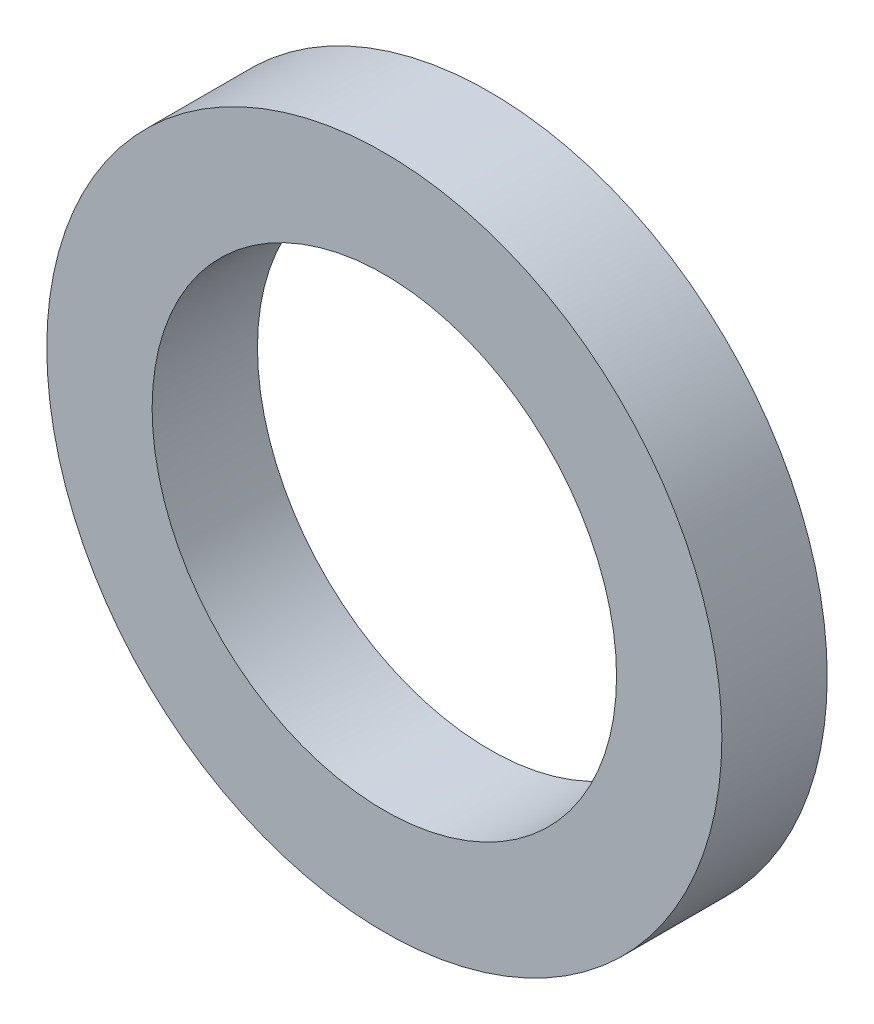
SolidWorks part; units mm, degrees
ref_plane "Front Plane" through (0, 0, 0) normal (0, 0, 1) x (1, 0, 0)
ref_plane "Top Plane" through (0, 0, 0) normal (0, 1, 0) x (1, 0, 0)
ref_plane "Right Plane" through (0, 0, 0) normal (1, 0, 0) x (0, 0, -1)
sketch "Sketch1" plane through (0, 0, 0) normal (0, 0, 1) x (1, 0, 0)
  line L0 (13.9055, 0) -> (52.0055, 0)
  line L1 (52.0055, 0) -> (52.0055, 25.4)
  line L2 (52.0055, 25.4) -> (26.6055, 76.2)
  line L3 (26.6055, 76.2) -> (13.9055, 76.2)
  line L4 (13.9055, 76.2) -> (13.9055, 63.5)
  line L8 (13.9055, 25.4) -> (13.9055, 0)
  line L9 (13.9055, 63.5) -> (22.1886, 51.6705)
  line L10 (22.1886, 51.6705) -> (22.1886, 37.2295)
  line L11 (22.1886, 37.2295) -> (13.9055, 25.4)
  line L12 (0, 0) -> (0, 106.6645) construction
  line L13 (-22.1886, 37.2295) -> (-13.9055, 25.4)
  line L14 (-22.1886, 51.6705) -> (-22.1886, 37.2295)
  line L15 (-13.9055, 63.5) -> (-22.1886, 51.6705)
  line L16 (-13.9055, 25.4) -> (-13.9055, 0)
  line L17 (-13.9055, 76.2) -> (-13.9055, 63.5)
  line L18 (-26.6055, 76.2) -> (-13.9055, 76.2)
  line L19 (-52.0055, 25.4) -> (-26.6055, 76.2)
  line L20 (-52.0055, 0) -> (-52.0055, 25.4)
  line L21 (-13.9055, 0) -> (-52.0055, 0)
  line L24 (-7.493, 16.8) -> (7.493, 16.8) construction
  line L25 (-7.493, 33.6) -> (7.493, 33.6) construction
  line L26 (-7.493, 33.6) -> (-7.493, 0) construction
  line L27 (-7.493, 0) -> (7.493, 0) construction
  line L28 (7.493, 33.6) -> (7.493, 0) construction
  line L30 (-33.493, 24.8) -> (-17.493, 24.8) construction
  line L31 (-33.493, 24.8) -> (-33.493, 8.8) construction
  line L32 (-33.493, 8.8) -> (-17.493, 8.8) construction
  line L33 (-17.493, 24.8) -> (-17.493, 8.8) construction
  line L34 (-33.493, 24.8) -> (-17.493, 8.8) construction
  line L35 (-33.493, 8.8) -> (-17.493, 24.8) construction
  line L36 (17.493, 24.8) -> (33.493, 24.8) construction
  line L37 (17.493, 24.8) -> (17.493, 8.8) construction
  line L38 (17.493, 8.8) -> (33.493, 8.8) construction
  line L39 (33.493, 24.8) -> (33.493, 8.8) construction
  line L40 (17.493, 24.8) -> (33.493, 8.8) construction
  line L41 (17.493, 8.8) -> (33.493, 24.8) construction
  circle A0 centre (-25.493, 16.8) radius 18 construction
  circle A1 centre (25.493, 16.8) radius 18 construction
  circle A2 centre (-33.493, 8.8) radius 2
  circle A3 centre (-17.493, 8.8) radius 2
  circle A4 centre (17.493, 8.8) radius 2
  circle A5 centre (33.493, 8.8) radius 2
  point P26 (0, 0)
  point P31 (-25.493, 16.8)
  point P32 (0, 16.8)
  dimension "D8" = 36
  dimension "D12" = 4
  dimension "D13" = 1.5875
  dimension "D2" = 38.1
  dimension "D3" = 25.4
  dimension "D4" = 12.7
  dimension "D5" = 38.1
  dimension "D6" = 145
  dimension "D7" = 145
  dimension "D9" = 14.986
  dimension "D10" = 33.6
  dimension "D11" = 16
extrude "Boss-Extrude1" add sketch "Sketch1" along normal mid plane 12.7 contours L10 L11 L8 L0 L1 L2 L3 L4 L9 A5 A4 | A4 | A5
sketch "Sketch2" plane through (0, 0, 0) normal (0, 0, 1) x (1, 0, 0)
  circle A0 centre (25.493, 16.8) radius 7
  dimension "D1" = 14
extrude "Cut-Extrude1" cut sketch "Sketch2" against normal through all both and the other way through all
sketch "Sketch5" plane through (0, 0, 6.35) normal (0, 0, 1) x (1, 0, 0)
  circle A0 centre (25.493, 16.8) radius 7 construction
  circle A1 centre (25.493, 16.8) radius 7
extrude "Boss-Extrude2" add sketch "Sketch5" along normal blind 31.75 and the other way up to surface (12.7 mm away) separate body other way up to face at (32.493, 16.8, -6.35)
ref_plane "Plane1" through (0, 0, 15.875) normal (0, 0, 1) x (1, 0, 0)
sketch "Sketch6" plane through (0, 0, 15.875) normal (0, 0, 1) x (1, 0, 0)
  line L0 (14.3805, 0) -> (-14.3805, 0)
  line L1 (14.3805, 30.15) -> (36.6055, 30.15)
  line L2 (14.3805, 30.15) -> (14.3805, 0)
  line L3 (14.3805, -22.225) -> (36.6055, -22.225)
  line L4 (36.6055, 30.15) -> (36.6055, -22.225)
  line L5 (36.6055, -22.225) -> (14.3805, -22.225)
  line L13 (14.3805, 0) -> (14.3805, -22.225) construction
  line L14 (25.493, 30.15) -> (25.493, -22.225) construction
  line L15 (0, 0) -> (0, -22.225)
  line L16 (-14.3805, -22.225) -> (14.3805, -22.225)
  line L17 (0, 0) -> (0, 106.6645) construction
  line L18 (0, 0) -> (0, 106.6645) construction
  line L19 (-25.493, 30.15) -> (-25.493, -22.225) construction
  line L20 (-14.3805, 0) -> (-14.3805, -22.225) construction
  line L22 (-36.6055, -22.225) -> (-14.3805, -22.225)
  line L23 (-36.6055, 30.15) -> (-36.6055, -22.225)
  line L24 (-14.3805, -22.225) -> (-36.6055, -22.225)
  line L25 (-14.3805, 30.15) -> (-14.3805, 0)
  line L26 (-14.3805, 30.15) -> (-36.6055, 30.15)
  circle A1 centre (25.493, 16.8) radius 7 construction
  circle A2 centre (25.493, 16.8) radius 7
  circle A3 centre (-25.493, 16.8) radius 7
  dimension "D2" = 6.35
  dimension "D1" = 22.225
extrude "Boss-Extrude3" add sketch "Sketch6" along normal mid plane 12.7 separate body contours L25 L26 L23 L22 L16 L15 L0 A3 | L15 L16 L3 L4 L1 L2 L0 A2
fillet "Fillet1" radius 6.35 8 edges at (-14.3805, 0, 15.875) (14.3805, 0, 15.875) (14.3805, 30.15, 15.875) (36.6055, -22.225, 15.875) (-36.6055, -22.225, 15.875) (-36.6055, 30.15, 15.875) (-14.3805, 30.15, 15.875) (36.6055, 30.15, 15.875)
fillet "Fillet2" radius 3.175 9 edges at (22.1886, 51.6705, 0) (13.9055, 63.5, 0) (13.9055, 76.2, 0) (52.0055, 25.4, 0) (52.0055, 0, 0) (13.9055, 0, 0) (13.9055, 25.4, 0) (22.1886, 37.2295, 0) (26.6055, 76.2, 0)
sketch "Sketch7" plane through (0, 0, 6.35) normal (0, 0, 1) x (1, 0, 0)
  circle A0 centre (25.493, 16.8) radius 7 construction
  circle A1 centre (25.493, 16.8) radius 7
  circle A2 centre (25.493, 16.8) radius 10.175
  dimension "D1" = 3.175
extrude "Boss-Extrude4" add sketch "Sketch7" along normal up to surface (3.175 mm away) separate body
delete or keep bodies "Body-Delete/Keep 1" type delete bodies bodies 109 111 110
